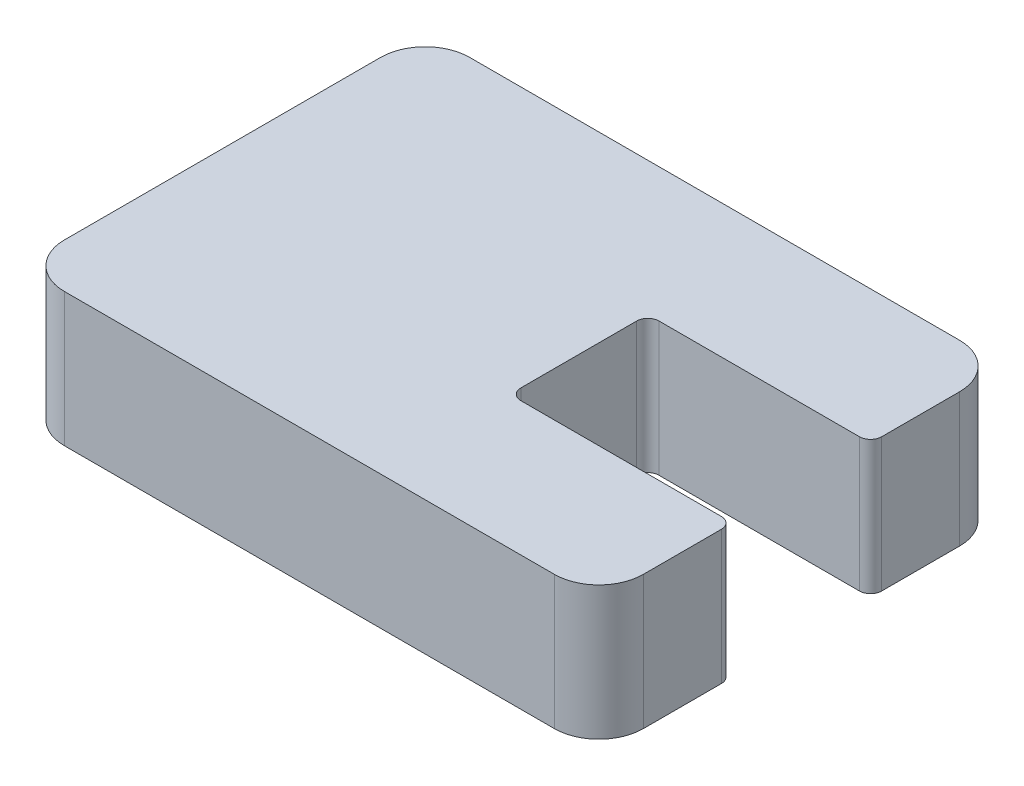
SolidWorks part; units mm, degrees
ref_plane "Alzado" through (0, 0, 0) normal (0, 0, 1) x (1, 0, 0)
ref_plane "Planta" through (0, 0, 0) normal (0, 1, 0) x (1, 0, 0)
ref_plane "Vista lateral" through (0, 0, 0) normal (1, 0, 0) x (0, 0, -1)
sketch "Croquis1" plane through (0, 0, 0) normal (0, 1, 0) x (1, 0, 0)
  line L0 (0, 3.55) -> (0, -3.55)
  line L1 (1, -4.55) -> (12, -4.55)
  line L2 (13, -3.55) -> (13, -1.55)
  line L3 (13, -1.55) -> (8, -1.55)
  line L4 (8, -1.55) -> (8, 1.55)
  line L5 (8, 1.55) -> (13, 1.55)
  line L6 (13, 1.55) -> (13, 3.55)
  line L7 (12, 4.55) -> (1, 4.55)
  arc A0 (12, -4.55) -> (13, -3.55) centre (12, -3.55) ccw
  arc A1 (0, -3.55) -> (1, -4.55) centre (1, -3.55) ccw
  arc A2 (0, 3.55) -> (1, 4.55) centre (1, 3.55) cw
  arc A3 (13, 3.55) -> (12, 4.55) centre (12, 3.55) ccw
  point P4 (0, 0)
  point P12 (13, -4.55)
  point P17 (0, 4.55)
  point P20 (13, 4.55)
  dimension "D7" = 1
  dimension "D8" = 1
  dimension "D1" = 3
  dimension "D2" = 3.1
  dimension "D3" = 3
  dimension "D4" = 13
  dimension "D5" = 5
  dimension "D6" = 5
extrude "Saliente-Extruir1" add sketch "Croquis1" along normal blind 3
fillet "Redondeo1" radius 0.25 4 edges at (13, 1.5, 1.55) (13, 1.5, -1.55) (8, 1.5, 1.55) (8, 1.5, -1.55)
